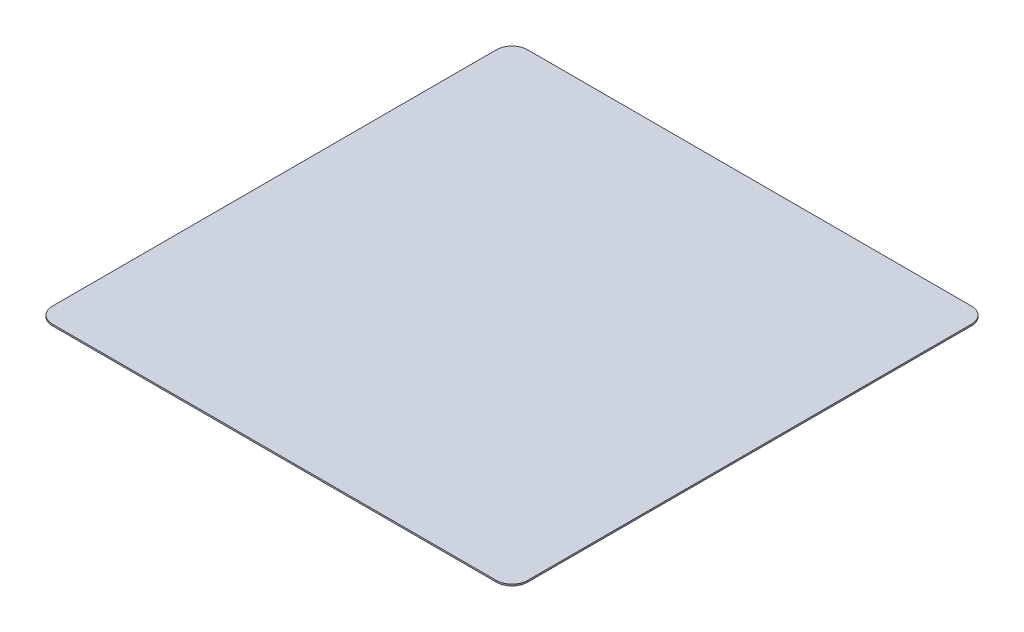
SolidWorks part; units mm, degrees
ref_plane "Front" through (0, 0, 0) normal (0, 0, 1) x (1, 0, 0)
ref_plane "Top" through (0, 0, 0) normal (0, 1, 0) x (1, 0, 0)
ref_plane "Right" through (0, 0, 0) normal (1, 0, 0) x (0, 0, -1)
sketch "Sketch1" plane through (0, 0, 0) normal (0, 1, 0) x (1, 0, 0)
  line L1 (0, 0) -> (305, 0)
  line L2 (0, 0) -> (0, 305)
  line L3 (0, 305) -> (305, 305)
  line L4 (305, 0) -> (305, 305)
  dimension "D1" = 305
extrude "Boss-Extrude1" add sketch "Sketch1" along normal blind 1
fillet "Fillet1" radius 10 4 edges at (0, 0.5, -305) (305, 0.5, -305) (305, 0.5, 0) (0, 0.5, 0)
